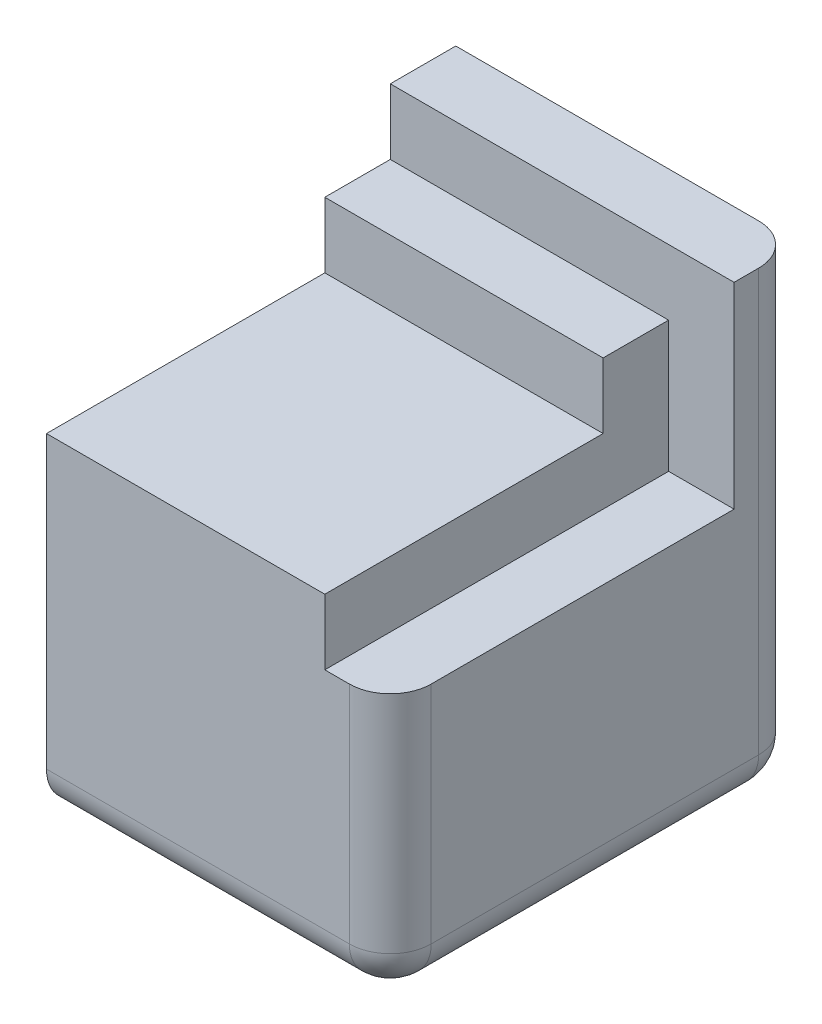
SolidWorks part; units mm, degrees
ref_plane "Front Plane" through (0, 0, 0) normal (0, 0, 1) x (1, 0, 0)
ref_plane "Top Plane" through (0, 0, 0) normal (0, 1, 0) x (1, 0, 0)
ref_plane "Right Plane" through (0, 0, 0) normal (1, 0, 0) x (0, 0, -1)
sketch "Sketch1" plane through (0, 0, 0) normal (0, 1, 0) x (1, 0, 0)
  line L1 (-4.2, -5) -> (4.2, -5)
  line L2 (-4.2, -5) -> (-4.2, 5)
  line L3 (-4.2, 5) -> (4.2, 5)
  line L4 (4.2, -5) -> (4.2, 5)
  line L5 (-4.2, -5) -> (4.2, 5) construction
  line L6 (-4.2, 5) -> (4.2, -5) construction
  point P0 (0, 0)
extrude "Boss-Extrude1" add sketch "Sketch1" along normal blind 11.3
sketch "Sketch4" plane through (4.2, 0, 0) normal (1, 0, 0) x (0, 0, -1)
  line L0 (5, 11.3) -> (5, 0) construction
  line L1 (-5, 11.3) -> (3.4, 11.3)
  line L2 (-5, 11.3) -> (-5, 9.7)
  line L3 (-5, 9.7) -> (3.4, 9.7)
  line L4 (3.4, 11.3) -> (3.4, 9.7)
  dimension "D1" = 1.6
extrude "Cut-Extrude1" cut sketch "Sketch4" against normal blind 11.3
sketch "Sketch5" plane through (4.2, 0, 0) normal (1, 0, 0) x (0, 0, -1)
  line L0 (-5, 9.7) -> (-5, 0) construction
  line L1 (-5, 6.5) -> (3.4, 6.5)
  line L2 (-5, 6.5) -> (-5, 9.7)
  line L3 (-5, 9.7) -> (3.4, 9.7)
  line L4 (3.4, 6.5) -> (3.4, 9.7)
  line L5 (-5, 0) -> (5, 0) construction
  dimension "D1" = 6.5
extrude "Cut-Extrude2" cut sketch "Sketch5" against normal blind 1.6
sketch "Sketch6" plane through (2.6, 0, 0) normal (1, 0, 0) x (0, 0, -1)
  line L0 (-5, 9.7) -> (-5, 6.5) construction
  line L1 (3.4, 9.7) -> (-5, 9.7)
  line L2 (3.4, 9.7) -> (3.4, 8.1)
  line L3 (3.4, 8.1) -> (-5, 8.1)
  line L4 (-5, 9.7) -> (-5, 8.1)
  line L5 (-5, 6.5) -> (3.4, 6.5) construction
  dimension "D1" = 1.6
extrude "Cut-Extrude3" cut sketch "Sketch6" against normal blind 6.8
sketch "Sketch7" plane through (0, 0, -3.4) normal (0, 0, 1) x (1, 0, 0)
  line L0 (-4.2, 8.1) -> (-4.2, 11.3) construction
  line L1 (2.6, 8.1) -> (-4.2, 8.1)
  line L2 (2.6, 8.1) -> (2.6, 9.7)
  line L3 (2.6, 9.7) -> (-4.2, 9.7)
  line L4 (-4.2, 8.1) -> (-4.2, 9.7)
extrude "Boss-Extrude2" add sketch "Sketch7" along normal blind 1.6
fillet "Fillet1" radius 1 5 edges at (0, 0, -5) (0, 0, 5) (4.2, 0, 0) (4.2, 3.25, 5) (4.2, 5.65, -5)
hole_wizard "M3x0.5 Tapped Hole1" positions "Sketch9" profile "Sketch8" tap size "M3x0.5" standard "ANSI Metric"
sketch "Sketch9" plane through (-4.2, 0, 0) normal (-1, 0, 0) x (0, 0, 1)
  line L0 (-4, 0) -> (4, 0) construction
  point P0 (0, 5)
  dimension "D1" = 5
sketch "Sketch8" plane through (-4.2, 5, 0) normal (0, 1, 0) x (0, 0, 1)
  line L0 (0, 0) -> (0, 7.2511)
  line L1 (0, 7.2511) -> (1.25, 6.5)
  line L2 (1.25, 6.5) -> (1.25, 0)
  line L5 (1.25, 0) -> (0, 0)
  line L10 (0, 7.2511) -> (-1.25, 6.5) construction
  line L11 (0, -6.35) -> (0, 107.95) construction
  dimension "Tap Drill Dia." = 2.5
  dimension "Tap Drill Depth" = 6.5
  dimension "Drill Angle" = 118
cosmetic thread "Hole Thread1" parameters "D1"=5, "D2"=3
